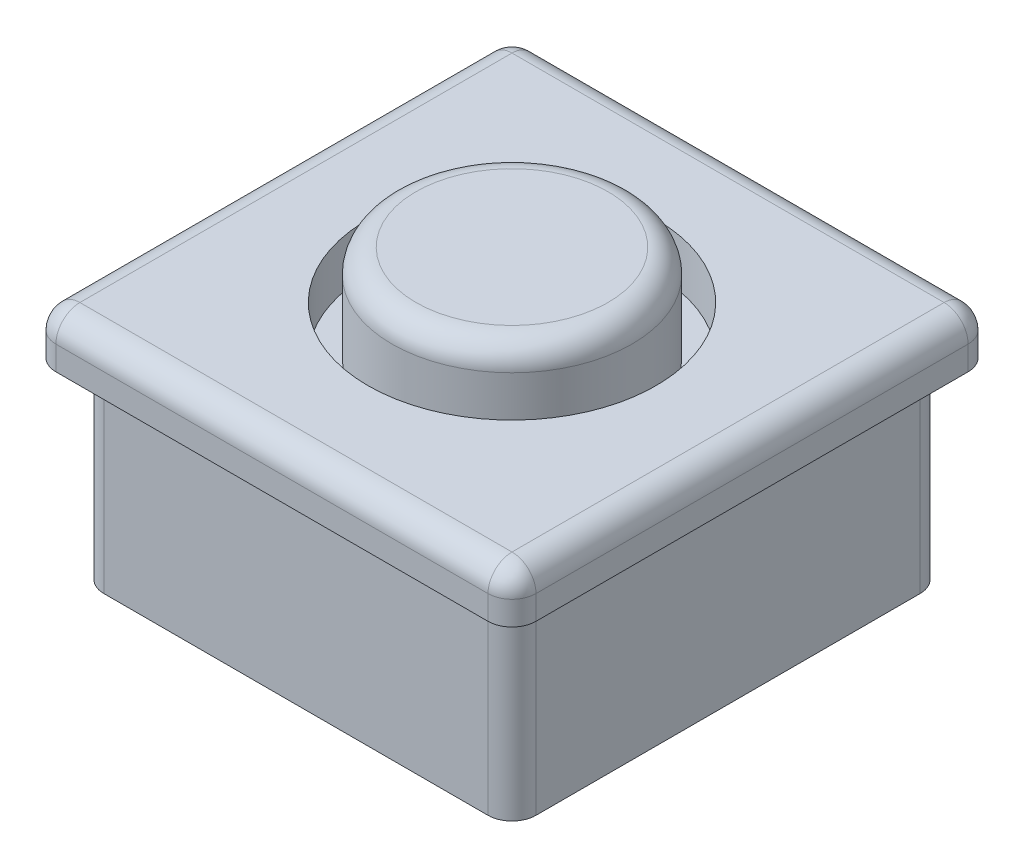
SolidWorks part; units mm, degrees
ref_plane "Front Plane" through (0, 0, 0) normal (0, 0, 1) x (1, 0, 0)
ref_plane "Top Plane" through (0, 0, 0) normal (0, 1, 0) x (1, 0, 0)
ref_plane "Right Plane" through (0, 0, 0) normal (1, 0, 0) x (0, 0, -1)
sketch "Sketch1" plane through (0, 0, 0) normal (0, 1, 0) x (1, 0, 0)
  line L1 (1, 0) -> (19, 0)
  line L2 (0, 1) -> (0, 19)
  line L3 (1, 20) -> (19, 20)
  line L4 (20, 1) -> (20, 19)
  arc A0 (1, 0) -> (0, 1) centre (1, 1) cw
  arc A1 (0, 19) -> (1, 20) centre (1, 19) cw
  arc A2 (19, 20) -> (20, 19) centre (19, 19) cw
  arc A3 (19, 0) -> (20, 1) centre (19, 1) ccw
  circle A4 centre (10, 10) radius 6
  point P7 (0, 0)
  point P10 (0, 20)
  point P15 (20, 0)
  point P18 (0, 0)
  point P19 (0, 10)
  point P20 (0, 0)
  point P21 (10, 0)
  dimension "D3" = 1
  dimension "D4" = 12
  dimension "D1" = 20
  dimension "D2" = 20
extrude "Boss-Extrude1" add sketch "Sketch1" along normal blind 2
sketch "Sketch2" plane through (0, 0, 0) normal (0, 1, 0) x (1, 0, 0)
  line L0 (1, 0) -> (19, 0) construction
  line L1 (2, 1) -> (18, 1)
  line L2 (1, 2) -> (1, 18)
  line L3 (2, 19) -> (18, 19)
  line L4 (19, 2) -> (19, 18)
  line L5 (0, 19) -> (0, 1) construction
  arc A0 (18, 1) -> (19, 2) centre (18, 2) ccw
  arc A1 (19, 18) -> (18, 19) centre (18, 18) ccw
  arc A2 (2, 19) -> (1, 18) centre (2, 18) ccw
  arc A3 (2, 1) -> (1, 2) centre (2, 2) cw
  point P10 (19, 1)
  point P15 (1, 19)
  point P18 (1, 1)
  dimension "D5" = 1
  dimension "D1" = 18
  dimension "D2" = 18
  dimension "D3" = 1
  dimension "D4" = 1
extrude "Boss-Extrude2" add sketch "Sketch2" against normal blind 8
sketch "Sketch3" plane through (0, 0, 0) normal (0, 1, 0) x (1, 0, 0)
  circle A0 centre (10, 10) radius 5
  dimension "D1" = 10
extrude "Boss-Extrude3" add sketch "Sketch3" along normal blind 4
fillet "Fillet1" radius 1 9 edges at (19.7071, 2, -0.2929) (10, 2, 0) (0.2929, 2, -0.2929) (0, 2, -10) (0.2929, 2, -19.7071) (10, 2, -20) (19.7071, 2, -19.7071) (20, 2, -10) (10, 4, -5)
